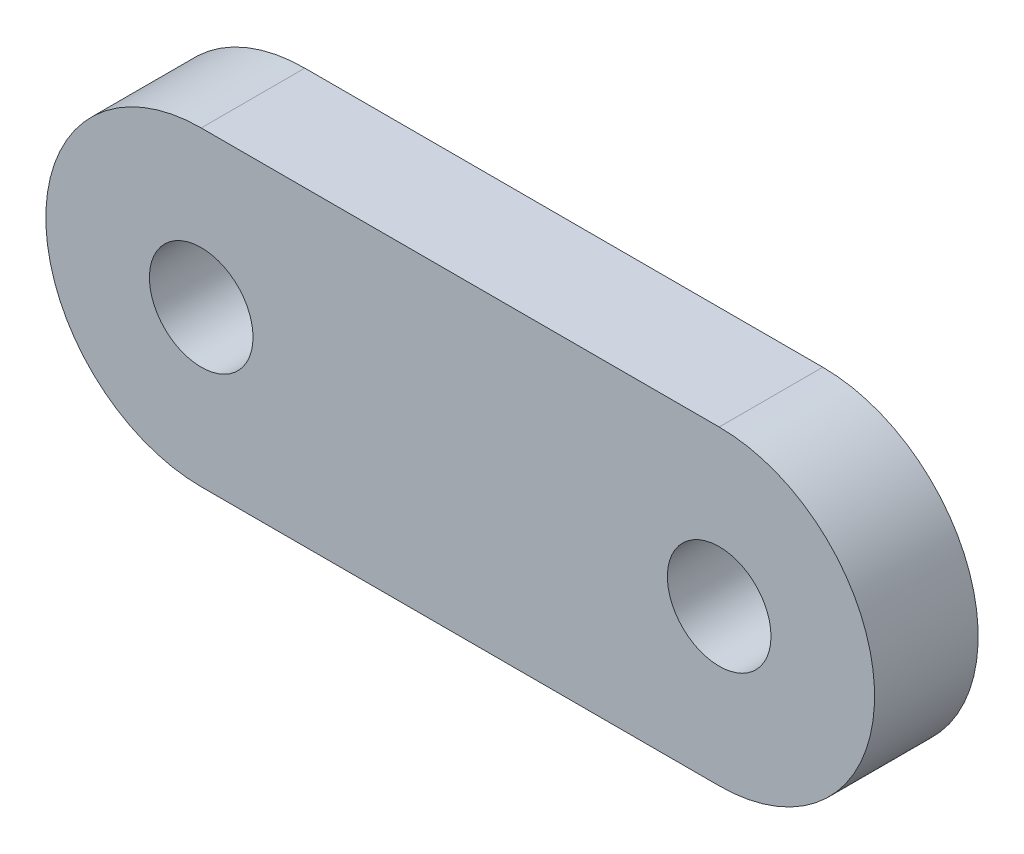
SolidWorks part; units mm, degrees
ref_plane "Front Plane" through (0, 0, 0) normal (0, 0, 1) x (1, 0, 0)
ref_plane "Top Plane" through (0, 0, 0) normal (0, 1, 0) x (1, 0, 0)
ref_plane "Right Plane" through (0, 0, 0) normal (1, 0, 0) x (0, 0, -1)
sketch "Sketch2" plane through (0, 0, 0) normal (0, 0, 1) x (1, 0, 0)
  line L0 (-15.875, 0) -> (15.875, 0) construction
  line L1 (-15.875, 9.525) -> (15.875, 9.525)
  line L2 (-15.875, -9.525) -> (15.875, -9.525)
  arc A0 (-15.875, 9.525) -> (-15.875, -9.525) centre (-15.875, 0) ccw
  arc A1 (15.875, -9.525) -> (15.875, 9.525) centre (15.875, 0) ccw
  point P2 (0, 0)
  dimension "D1" = 31.75
  dimension "D2" = 19.05
extrude "Boss-Extrude1" add sketch "Sketch2" along normal blind 6.35
sketch "Sketch3" plane through (0, 0, 6.35) normal (0, 0, 1) x (1, 0, 0)
  circle A0 centre (-15.875, 0) radius 3.175
  circle A1 centre (15.875, 0) radius 3.175
  dimension "D1" = 6.35
extrude "Cut-Extrude1" cut sketch "Sketch3" against normal through all
